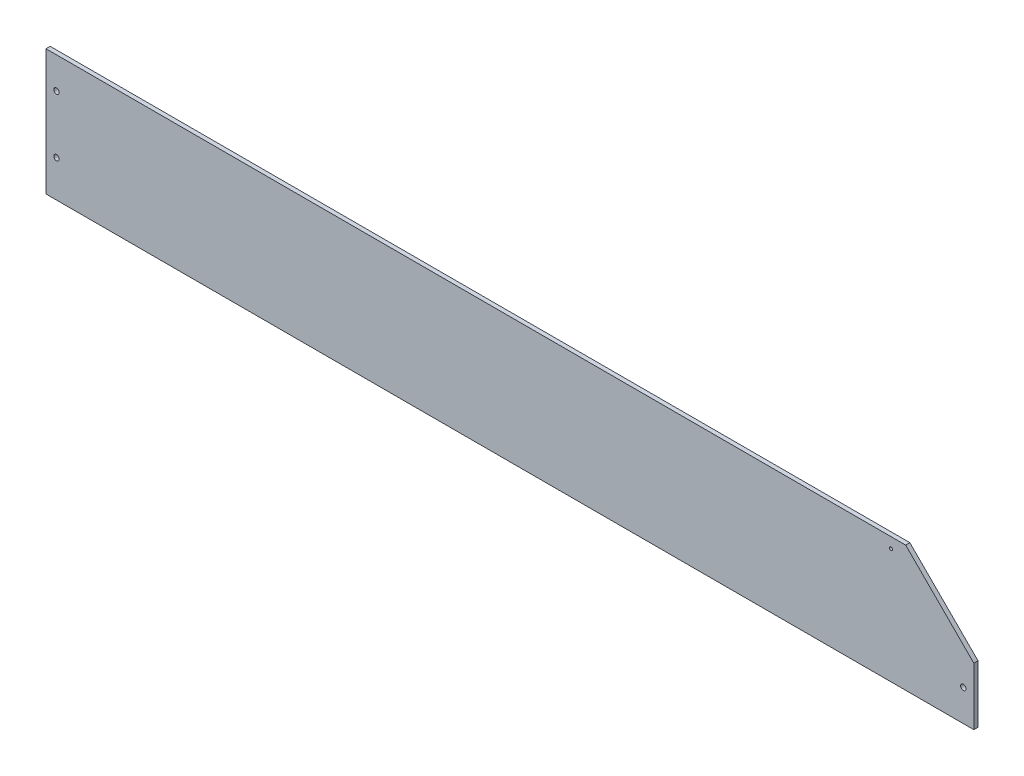
SolidWorks part; units mm, degrees
ref_plane "Front Plane" through (0, 0, 0) normal (0, 0, 1) x (1, 0, 0)
ref_plane "Top Plane" through (0, 0, 0) normal (0, 1, 0) x (1, 0, 0)
ref_plane "Right Plane" through (0, 0, 0) normal (1, 0, 0) x (0, 0, -1)
sketch "Sketch1" plane through (0, 0, 0) normal (0, 0, 1) x (1, 0, 0)
  line L0 (0, 0) -> (885, 0)
  line L1 (885, 0) -> (885, 55)
  line L2 (885, 55) -> (820, 120)
  line L3 (820, 120) -> (0, 120)
  line L4 (0, 120) -> (0, 0)
  dimension "D1" = 120
  dimension "D2" = 885
  dimension "D3" = 55
  dimension "D4" = 135
extrude "Boss-Extrude1" add sketch "Sketch1" along normal blind 4
sketch "Sketch2" plane through (0, 0, 0) normal (0, 0, -1) x (-1, 0, 0)
  line L0 (0, 120) -> (0, 0) construction
  line L1 (-25, 85) -> (-20, 85)
  line L2 (-25, 85) -> (-25, 95)
  line L3 (-25, 95) -> (-20, 95)
  line L4 (-20, 85) -> (-20, 95)
  line L5 (-20, 30) -> (-25, 30)
  line L6 (-20, 30) -> (-20, 40)
  line L7 (-20, 40) -> (-25, 40)
  line L8 (-25, 30) -> (-25, 40)
  line L9 (-820, 120) -> (0, 120) construction
  point P10 (-20, 90)
  point P13 (-20, 35)
  dimension "D1" = 5
  dimension "D2" = 5
  dimension "D3" = 10
  dimension "D4" = 10
  dimension "D5" = 20
  dimension "D6" = 20
  dimension "D7" = 30
  dimension "D8" = 85
sketch "Sketch4" plane through (0, 0, 0) normal (0, 0, -1) x (-1, 0, 0)
  line L0 (-885, 0) -> (-885, 55) construction
  line L1 (-865, 35) -> (-860, 35)
  line L2 (-865, 35) -> (-865, 25)
  line L3 (-865, 25) -> (-860, 25)
  line L4 (-860, 35) -> (-860, 25)
  dimension "D1" = 10
  dimension "D2" = 5
  dimension "D3" = 20
  dimension "D4" = 20
move or copy body "Body-Move/Copy1" bodies to move or copy 102 parameters "D1"=0, "D2"=0, "D3"=0
sketch "Sketch8" plane through (0, 0, 0) normal (0, 0, 1) x (1, 0, 0)
  line L0 (820, 120) -> (0, 120) construction
  line L1 (0, 120) -> (0, 0) construction
  circle A0 centre (10, 90) radius 2.6
  circle A1 centre (10, 35) radius 2.6
  dimension "D5" = 5.2
  dimension "D6" = 5.2
  dimension "D1" = 30
  dimension "D2" = 85
  dimension "D3" = 10
  dimension "D4" = 10
extrude "Cut-Extrude4" cut sketch "Sketch8" against normal blind 10
sketch "Sketch9" plane through (0, 0, 0) normal (0, 0, 1) x (1, 0, 0)
  line L0 (885, 0) -> (885, 55) construction
  line L2 (885, 55) -> (860.8873, 55)
  circle A0 centre (875, 30) radius 2.6
  dimension "D3" = 5.2
  dimension "D1" = 10
  dimension "D2" = 25
extrude "Cut-Extrude5" cut sketch "Sketch9" against normal blind 10 contours A0
sketch "Sketch10" plane through (0, 0, 0) normal (0, 0, 1) x (1, 0, 0)
  line L0 (820, 120) -> (0, 120) construction
  circle A0 centre (806, 110) radius 1.5
  dimension "D3" = 3
  dimension "D1" = 14
  dimension "D2" = 10
extrude "Cut-Extrude6" cut sketch "Sketch10" against normal through all
